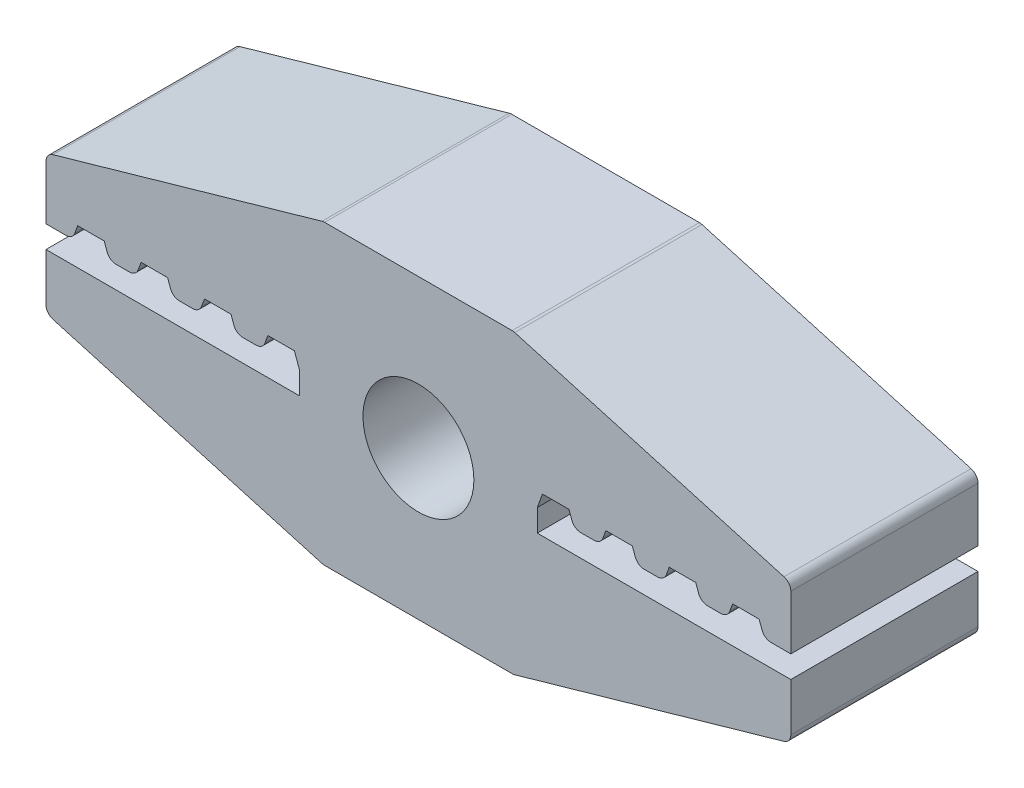
SolidWorks part; units mm, degrees
ref_plane "Front Plane" through (0, 0, 0) normal (0, 0, 1) x (1, 0, 0)
ref_plane "Top Plane" through (0, 0, 0) normal (0, 1, 0) x (1, 0, 0)
ref_plane "Right Plane" through (0, 0, 0) normal (1, 0, 0) x (0, 0, -1)
sketch "Sketch1" plane through (0, 0, 0) normal (0, 0, 1) x (1, 0, 0)
  line L1 (-11.938, -4.7625) -> (11.938, -4.7625)
  line L2 (-11.938, -4.7625) -> (-11.938, 4.7625)
  line L3 (-11.938, 4.7625) -> (11.938, 4.7625)
  line L4 (11.938, -4.7625) -> (11.938, 4.7625)
  line L5 (-11.938, -4.7625) -> (11.938, 4.7625) construction
  line L6 (-11.938, 4.7625) -> (11.938, -4.7625) construction
  circle A0 centre (0, 0) radius 1.778
  dimension "D1" = 3.556
  dimension "D2" = 9.525
  dimension "D3" = 23.876
extrude "Boss-Extrude1" add sketch "Sketch1" along normal blind 6
sketch "Sketch2" plane through (0, 0, 6) normal (0, 0, 1) x (1, 0, 0)
  line L0 (0, 0) -> (-11.938, 0) construction
  line L1 (-11.938, 4.7625) -> (-11.938, -4.7625) construction
  line L2 (-11.938, -0.4572) -> (-3.81, -0.4572)
  line L3 (-3.81, -0.4572) -> (-3.81, 0)
  line L4 (-3.9764, 0.7112) -> (-3.81, 0.254)
  line L5 (-3.9764, 0.7112) -> (-4.826, 0.7112)
  line L6 (-4.826, 0.7112) -> (-4.9924, 0.254)
  line L7 (-4.9924, 0.254) -> (-5.842, 0.254)
  line L8 (-3.81, 0.254) -> (-3.81, 0)
  line L9 (-6.0084, 0.7112) -> (-5.842, 0.254)
  line L10 (-6.0084, 0.7112) -> (-6.858, 0.7112)
  line L11 (-6.858, 0.7112) -> (-7.0244, 0.254)
  line L12 (-7.0244, 0.254) -> (-7.874, 0.254)
  line L13 (-8.0404, 0.7112) -> (-7.874, 0.254)
  line L14 (-8.0404, 0.7112) -> (-8.89, 0.7112)
  line L15 (-8.89, 0.7112) -> (-9.0564, 0.254)
  line L16 (-9.0564, 0.254) -> (-9.906, 0.254)
  line L17 (-10.0724, 0.7112) -> (-9.906, 0.254)
  line L18 (-10.0724, 0.7112) -> (-10.922, 0.7112)
  line L19 (-10.922, 0.7112) -> (-11.0884, 0.254)
  line L20 (-11.0884, 0.254) -> (-11.938, 0.254)
  line L21 (-11.938, 0.254) -> (-11.938, -0.4572)
  line L22 (-11.938, 4.7625) -> (-11.938, 2.2225)
  line L23 (-11.938, 2.2225) -> (-3.048, 4.7625)
  line L24 (11.938, 4.7625) -> (-11.938, 4.7625) construction
  line L25 (-3.048, 4.7625) -> (-11.938, 4.7625)
  line L26 (-11.938, -2.2225) -> (-11.938, -4.7625)
  line L27 (-11.938, -4.7625) -> (-3.048, -4.7625)
  line L28 (-11.938, -4.7625) -> (11.938, -4.7625) construction
  line L29 (-3.048, -4.7625) -> (-11.938, -2.2225)
  dimension "D1" = 0.4572
  dimension "D2" = 3.81
  dimension "D3" = 0.254
  dimension "D4" = 0.4572
  dimension "D5" = 70
  dimension "D6" = 70
  dimension "D7" = 2.032
  dimension "D9" = 2.54
  dimension "D10" = 8.89
  dimension "D8" = 4
extrude "Cut-Extrude3" cut sketch "Sketch2" against normal through all
mirror "Mirror1" about plane through (0, 0, 0) normal (1, 0, 0) of "Cut-Extrude3"
fillet "Fillet1" radius 0.3048 22 edges at (-3.048, 4.7625, 3) (3.048, 4.7625, 3) (11.938, 2.2225, 3) (11.938, -2.2225, 3) (3.048, -4.7625, 3) (-3.048, -4.7625, 3) (-11.938, -2.2225, 3) (-11.938, 2.2225, 3) (11.0884, 0.254, 3) (9.906, 0.254, 3) (9.0564, 0.254, 3) (7.874, 0.254, 3) (7.0244, 0.254, 3) (5.842, 0.254, 3) (4.9924, 0.254, 3) (-4.9924, 0.254, 3) (-5.842, 0.254, 3) (-7.0244, 0.254, 3) (-7.874, 0.254, 3) (-9.0564, 0.254, 3) (-9.906, 0.254, 3) (-11.0884, 0.254, 3)
